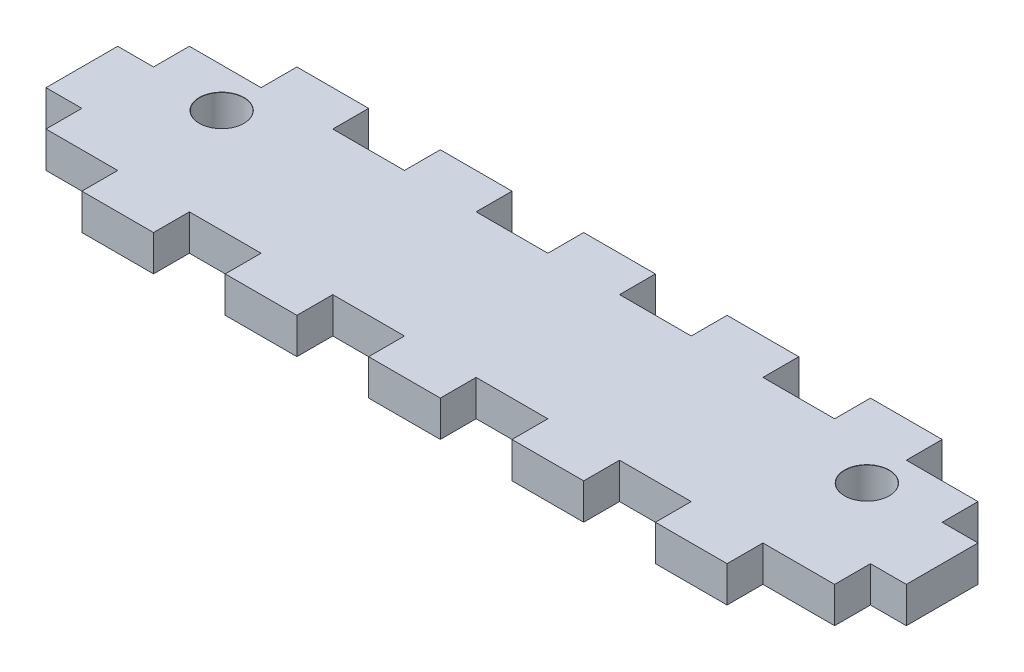
SolidWorks part; units mm, degrees
ref_plane "Front Plane" through (0, 0, 0) normal (0, 0, 1) x (1, 0, 0)
ref_plane "Top Plane" through (0, 0, 0) normal (0, 1, 0) x (1, 0, 0)
ref_plane "Right Plane" through (0, 0, 0) normal (1, 0, 0) x (0, 0, -1)
sketch "Sketch1" plane through (0, 0, 0) normal (0, 1, 0) x (1, 0, 0)
  line L0 (45, 15) -> (35, 15)
  line L1 (35, 15) -> (35, 10)
  line L2 (35, 10) -> (25, 10)
  line L3 (25, 10) -> (25, 15)
  line L4 (25, 15) -> (15, 15)
  line L5 (15, 15) -> (15, 10)
  line L6 (15, 10) -> (5, 10)
  line L7 (5, 10) -> (5, 15)
  line L8 (5, 15) -> (-5, 15)
  line L9 (-5, 15) -> (-5, 10)
  line L10 (-5, 10) -> (-15, 10)
  line L11 (-15, 10) -> (-15, 15)
  line L12 (-15, 15) -> (-25, 15)
  line L13 (-25, 15) -> (-25, 10)
  line L14 (-25, 10) -> (-35, 10)
  line L15 (-35, 10) -> (-35, 15)
  line L16 (-35, 15) -> (-45, 15)
  line L17 (-45, 15) -> (-45, 10)
  line L18 (-45, 10) -> (-55, 10)
  line L19 (-55, 10) -> (-55, 5)
  line L20 (-55, 5) -> (-60, 5)
  line L21 (-60, 5) -> (-60, -5)
  line L22 (-60, -5) -> (-55, -5)
  line L23 (-55, -5) -> (-55, -10)
  line L24 (-55, -10) -> (-45, -10)
  line L25 (-45, -10) -> (-45, -15)
  line L26 (-45, -15) -> (-35, -15)
  line L27 (-35, -15) -> (-35, -10)
  line L28 (-35, -10) -> (-25, -10)
  line L29 (-25, -10) -> (-25, -15)
  line L30 (-25, -15) -> (-15, -15)
  line L31 (-15, -15) -> (-15, -10)
  line L32 (-15, -10) -> (-5, -10)
  line L33 (-5, -10) -> (-5, -15)
  line L34 (-5, -15) -> (5, -15)
  line L35 (5, -15) -> (5, -10)
  line L36 (5, -10) -> (15, -10)
  line L37 (15, -10) -> (15, -15)
  line L38 (15, -15) -> (25, -15)
  line L39 (25, -15) -> (25, -10)
  line L40 (25, -10) -> (35, -10)
  line L41 (35, -10) -> (35, -15)
  line L42 (35, -15) -> (45, -15)
  line L43 (45, -15) -> (45, -10)
  line L44 (45, -10) -> (55, -10)
  line L45 (55, -10) -> (55, -5)
  line L46 (55, -5) -> (60, -5)
  line L47 (60, -5) -> (60, 5)
  line L48 (60, 5) -> (55, 5)
  line L49 (55, 5) -> (55, 10)
  line L50 (55, 10) -> (45, 10)
  line L51 (45, 10) -> (45, 15)
  line L52 (-60, 15) -> (60, -15) construction
  line L53 (-60, 5) -> (-60, 15) construction
  line L54 (-60, 15) -> (-45, 15) construction
  line L55 (45, -15) -> (60, -15) construction
  line L56 (60, -15) -> (60, -5) construction
  point P54 (0, 0)
  dimension "D1" = 0
extrude "Boss-Extrude1" add sketch "Sketch1" along normal mid plane 5
sketch "Sketch2" plane through (0, 2.5, 0) normal (0, 1, 0) x (1, 0, 0)
  text T0 "Front/Back"
extrude "Cut-Extrude1" [suppressed] cut sketch "Sketch2" against normal blind 3
sketch "Sketch3" plane through (0, 2.5, 0) normal (0, 1, 0) x (1, 0, 0)
  line L0 (-45, 4.5) -> (45, 4.5) construction
  line L1 (-60, 5) -> (-60, -5) construction
  line L3 (60, -5) -> (60, 5) construction
  line L4 (5, 15) -> (-5, 15) construction
  point P0 (-45, 4.5)
  point P1 (45, 4.5)
  dimension "D1" = 15
  dimension "D2" = 15
  dimension "D3" = 10.5
hole_wizard "Ø6.2 (6.2) Diameter Hole1" positions "Sketch3" profile "Sketch4" hole size "Ø6.2" standard "ISO" end condition through all
sketch "Sketch4" plane through (-45, 2.5, -4.5) normal (1, 0, 0) x (0, 0, 1)
  line L0 (0, 0) -> (0, 5)
  line L1 (0, 5) -> (3.1, 5)
  line L2 (3.1, 5) -> (3.1, 0.025)
  line L3 (3.1, 0.025) -> (3.125, 0)
  line L5 (3.125, 0) -> (0, 0)
  line L6 (-3.1, 0.025) -> (-3.125, 0) construction
  line L11 (0, -6.35) -> (0, 107.95) construction
  dimension "Thru Hole Dia." = 6.2
  dimension "Thru Hole Depth" = 5
  dimension "Near C'Sink Dia." = 6.25
  dimension "Near C'Sink Angle" = 90
